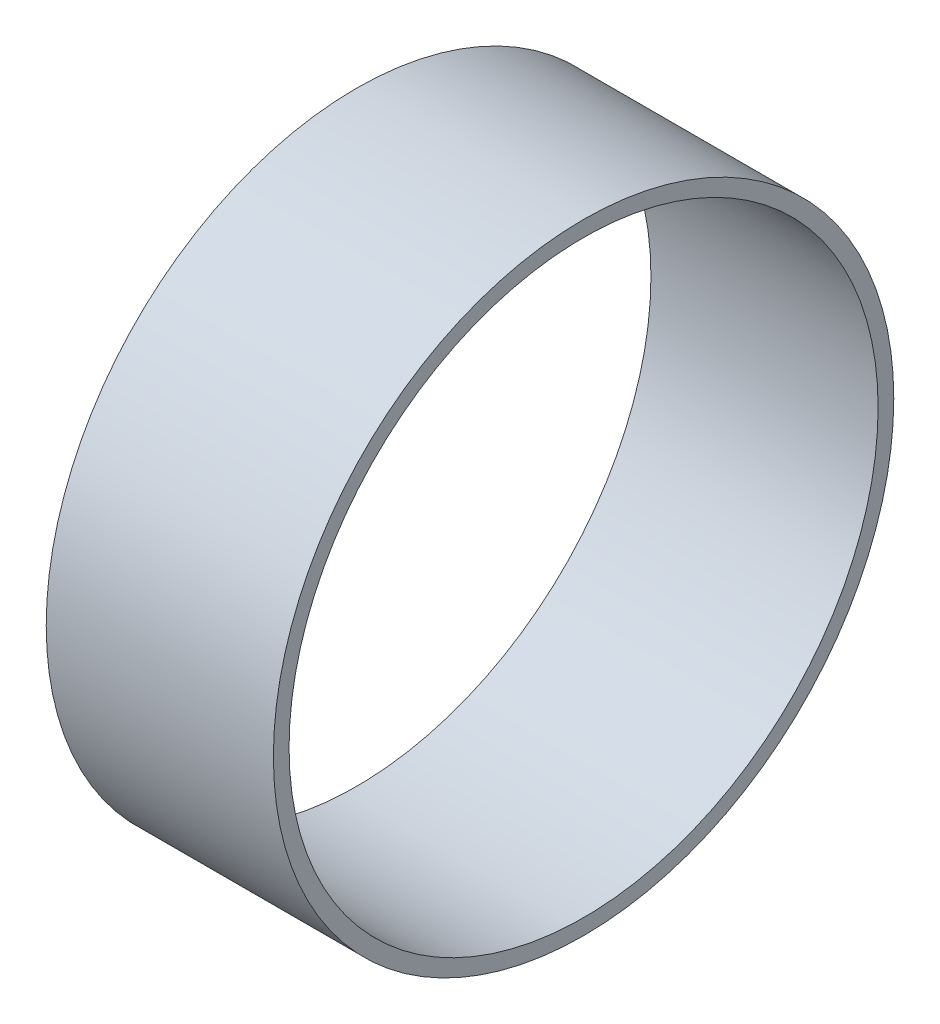
SolidWorks part; units mm, degrees
ref_plane "Plan1" through (0, 0, 0) normal (0, 0, 1) x (1, 0, 0)
ref_plane "Plan2" through (0, 0, 0) normal (0, 1, 0) x (1, 0, 0)
ref_plane "Plan3" through (0, 0, 0) normal (1, 0, 0) x (0, 0, -1)
sketch "Esquisse1" plane through (0, 0, 0) normal (0, 0, 1) x (1, 0, 0)
  line L0 (15, -19.8) -> (29.5, -19.8)
  line L1 (0, 0) -> (11.4214, 0) construction
  line L2 (6, 0) -> (6.6009, 0) construction
  line L3 (29.5, -14.3197) -> (29.5, -12.9732) construction
  line L4 (15, -13.542) -> (15, -14.5098) construction
  dimension "D1" = 19.8
revolve "Base-Révol.-Mince" add sketch "Esquisse1" angle 360 about L1
